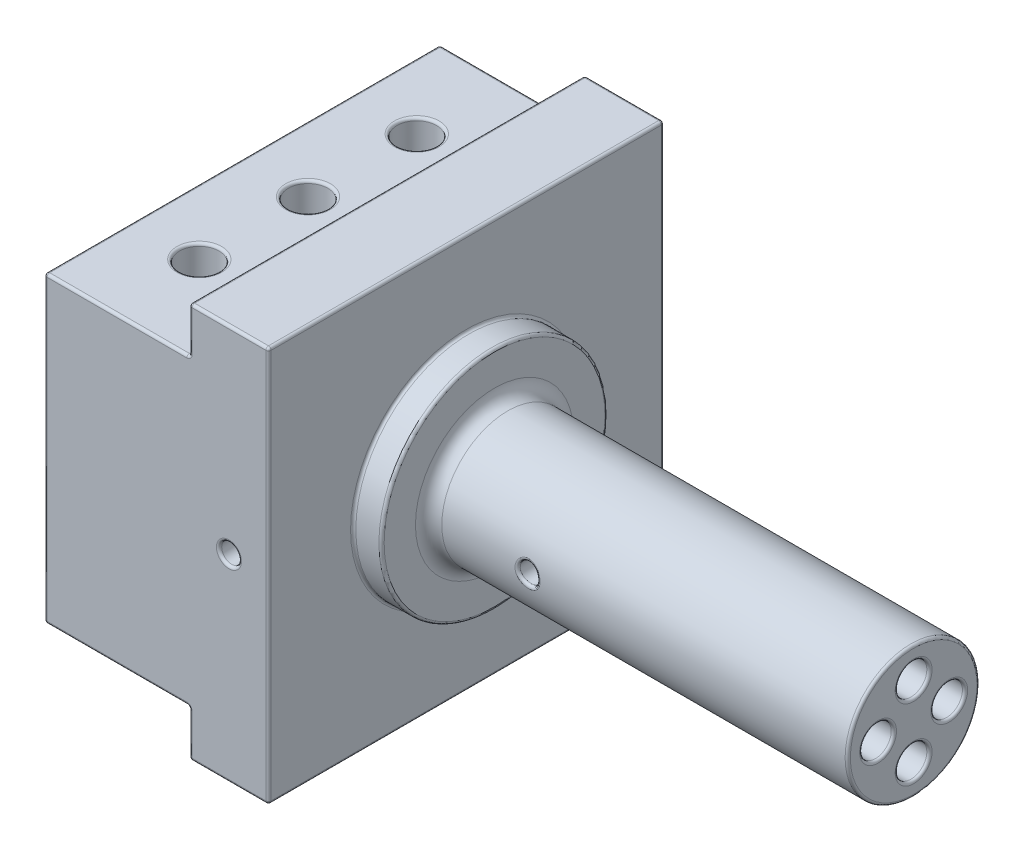
SolidWorks part; units mm, degrees
ref_plane "Front Plane" through (0, 0, 0) normal (0, 0, 1) x (1, 0, 0)
ref_plane "Top Plane" through (0, 0, 0) normal (0, 1, 0) x (1, 0, 0)
ref_plane "Right Plane" through (0, 0, 0) normal (1, 0, 0) x (0, 0, -1)
sketch "Sketch1" plane through (0, 0, 0) normal (1, 0, 0) x (0, 0, -1)
  circle A0 centre (0, 0) radius 10
  dimension "D1" = 20
extrude "Boss-Extrude1" add sketch "Sketch1" along normal blind 63.6
sketch "Sketch2" plane through (0, 0, 0) normal (-1, 0, 0) x (0, 0, 1)
  circle A0 centre (0, 0) radius 17.15
  dimension "D1" = 34.3
extrude "Boss-Extrude2" add sketch "Sketch2" along normal blind 4.3
fillet "Fillet1" radius 2 1 edges at (0, 0, -10)
sketch "Sketch3" plane through (-4.3, 0, 0) normal (-1, 0, 0) x (0, 0, 1)
  line L1 (-30, 30) -> (30, 30)
  line L2 (-30, 30) -> (-30, -30)
  line L3 (-30, -30) -> (30, -30)
  line L4 (30, 30) -> (30, -30)
  line L5 (-30, 30) -> (30, -30) construction
  line L6 (-30, -30) -> (30, 30) construction
  point P0 (0, 0)
  dimension "D1" = 60
extrude "Boss-Extrude3" add sketch "Sketch3" along normal blind 12
sketch "Sketch4" plane through (63.6, 0, 0) normal (1, 0, 0) x (0, 0, -1)
  line L0 (0, -5.4) -> (0, 0) construction
  line L1 (0, -10) -> (0, -7.8) construction
  circle A0 centre (0, -5.4) radius 2.4
  circle A1 centre (0, 0) radius 10 construction
  circle A2 centre (0, 0) radius 10 construction
  circle A3 centre (-5.4, 0) radius 2.4
  circle A4 centre (0, 5.4) radius 2.4
  circle A5 centre (5.4, 0) radius 2.4
  point P19 (0, 0)
  dimension "D1" = 4.8
  dimension "D2" = 2.2
  dimension "D3" = 4
extrude "Cut-Extrude1" cut sketch "Sketch4" against normal blind 5.7
sketch "Sketch5" plane through (0, 0, 0) normal (0, 1, 0) x (1, 0, 0)
  line L0 (0, 0) -> (-4.3, 0) construction
  line L1 (0, 0) -> (30, 0) construction
  line L2 (-4.3, 0) -> (-25, 0) construction
  line L4 (-4.3, -30) -> (-4.3, 30) construction
  line L5 (-25, 0) -> (-75.74, 0) construction
  line L6 (-75.74, 0) -> (-185, 0) construction
  dimension "D1" = 30
  dimension "D2" = 4.3
  dimension "D3" = 215
  dimension "D4" = 109.26
  dimension "D5" = 160
sketch "Sketch6" plane through (-16.3, 0, 0) normal (-1, 0, 0) x (0, 0, 1)
  line L0 (30, -30) -> (30, 30) construction
  line L1 (-30, -23) -> (30, -23)
  line L2 (-30, -23) -> (-30, 23)
  line L3 (-30, 23) -> (30, 23)
  line L4 (30, -23) -> (30, 23)
  line L5 (-30, -23) -> (30, 23) construction
  line L6 (-30, 23) -> (30, -23) construction
  point P0 (0, 0)
  dimension "D1" = 46
extrude "Boss-Extrude4" add sketch "Sketch6" along normal blind 22
sketch "Sketch7" plane through (0, -23, 0) normal (0, -1, 0) x (1, 0, 0)
  line L0 (-28.3, 30) -> (-28.3, 16.5) construction
  line L1 (-38.3, 30) -> (-16.3, 30) construction
  line L2 (-28.3, 16.5) -> (-28.3, 0) construction
  line L3 (-28.3, 0) -> (-28.3, -16.5) construction
  line L4 (-28.3, -16.5) -> (-28.3, -30) construction
  line L5 (-38.3, -30) -> (-16.3, -30) construction
  circle A0 centre (-28.3, -16.5) radius 3
  circle A1 centre (-28.3, 0) radius 3
  circle A2 centre (-28.3, 16.5) radius 3
  dimension "D2" = 12
  dimension "D3" = 6
  dimension "D1" = 13.5
  dimension "D4" = 16.5
extrude "Cut-Extrude2" cut sketch "Sketch7" against normal through all
ref_plane "Plane1" through (-185, 0, 0) normal (1, 0, 0) x (0, 0, -1)
sketch "Sketch8" plane through (0, 0, -30) normal (0, 0, -1) x (-1, 0, 0)
  line L0 (4.3, 0) -> (16.3, 0) construction
  line L1 (4.3, 30) -> (4.3, -30) construction
  circle A0 centre (10.3, 0) radius 1.5
  point P11 (10.3, 0)
  dimension "D1" = 3
extrude "Cut-Extrude3" cut sketch "Sketch8" against normal blind 5
mirror "Mirror1" about plane through (0, 0, 0) normal (0, 0, 1) of "Cut-Extrude3"
sketch "Sketch10" plane through (0, 0, 0) normal (0, 0, 1) x (1, 0, 0)
  line L0 (0, 0) -> (15, 0) construction
  circle A0 centre (15, 0) radius 1.5
  dimension "D1" = 3
  dimension "D2" = 15
extrude "Cut-Extrude5" cut sketch "Sketch10" against normal through all both and the other way through all
fillet "Fillet2" radius 0.4 47 edges at (63.6, 0, 3) (57.9, 0, 3) (63.6, -5.4, -2.4) (57.9, -5.4, -2.4) (63.6, 0, -7.8) (57.9, 0, -7.8) (63.6, 5.4, -2.4) (57.9, 5.4, -2.4) (-16.3, 30, 0) (-4.3, 30, 0) (-16.3, -30, 0) (-4.3, -30, 0) (-10.3, 30, -30) (-16.3, 26.5, -30) (-27.3, 23, -30) (-27.3, -23, -30) (-16.3, -26.5, -30) (-10.3, -30, -30) (-4.3, 0, -30) (-10.3, -30, 30) (-16.3, -26.5, 30) (-27.3, -23, 30) (-27.3, 23, 30) (-16.3, 26.5, 30) (-10.3, 30, 30) (-4.3, 0, 30) (-38.3, -23, 0) (-38.3, 0, -30) (-38.3, 23, 0) (-38.3, 0, 30) (-28.3, 23, -19.5) (-28.3, -23, -19.5) (-28.3, 23, -3) (-28.3, -23, -3) (-28.3, 23, 13.5) (-28.3, -23, 13.5) (63.6, 0, -10) (0, 0, 17.15) (-4.3, 0, 17.15) (-16.3, 23, 0) (-16.3, -23, 0) (-10.3, 1.5, -30) (-10.3, 1.5, 30) (-10.3, 1.5, -25) (-10.3, 1.5, 25) (13.5359, 0.3261, 9.9947) (13.5359, -0.3261, -9.9947)
